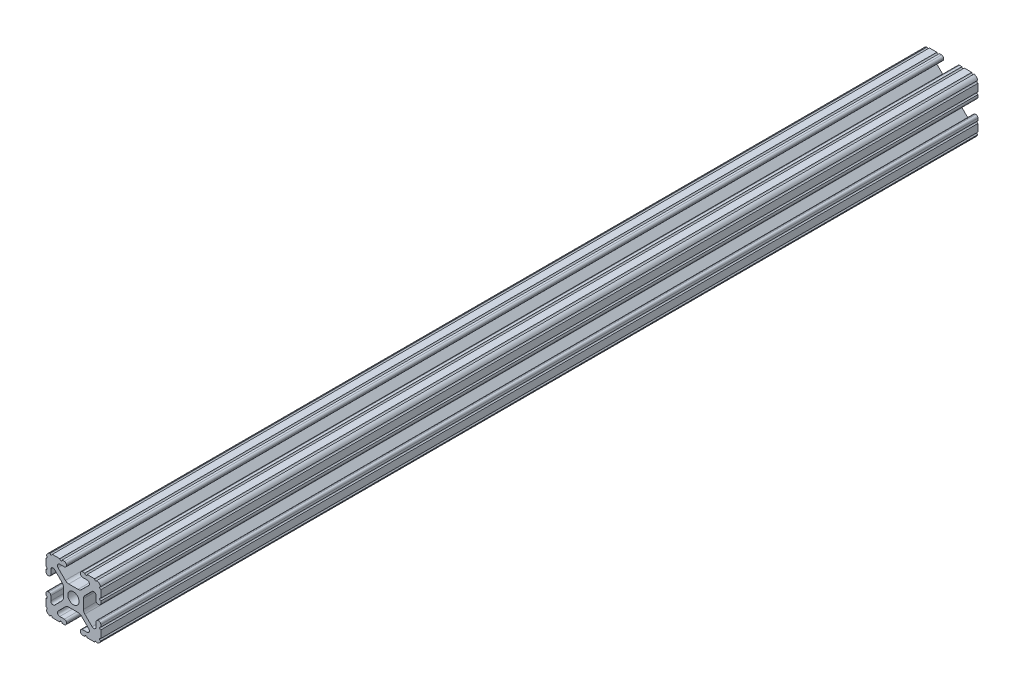
SolidWorks part; units mm, degrees
ref_plane "Front Plane" through (0, 0, 0) normal (0, 0, 1) x (1, 0, 0)
ref_plane "Top Plane" through (0, 0, 0) normal (0, 1, 0) x (1, 0, 0)
ref_plane "Right Plane" through (0, 0, 0) normal (1, 0, 0) x (0, 0, -1)
sketch "Sketch2" plane through (0, 0, 0) normal (0, 0, 1) x (1, 0, 0)
  line L0 (0, 12.7) -> (0, -12.7) construction
  line L1 (-12.7, 0) -> (12.7, 0) construction
  line L2 (3.2512, -12.7) -> (12.7, -12.7)
  line L3 (12.7, -12.7) -> (12.7, -3.2512)
  line L4 (3.2512, -12.7) -> (3.2512, -10.4902)
  line L5 (3.2512, -10.4902) -> (8.9276, -10.4902)
  line L6 (8.9276, -10.4902) -> (3.0856, -4.6482)
  line L7 (0, 0) -> (12.7, -12.7) construction
  line L8 (12.7, -3.2512) -> (10.4902, -3.2512)
  line L9 (10.4902, -3.2512) -> (10.4902, -8.9276)
  line L10 (10.4902, -8.9276) -> (4.6482, -3.0856)
  circle A0 centre (0, 0) radius 2.6035
  arc A1 (6.3485, -10.4902) -> (7.1039, -8.6665) centre (6.3485, -9.4219) ccw construction
  point P8 (0, -4.6482)
  dimension "Center Hole Diameter" = 5.207
  dimension "Rail Height" = 25.4
  dimension "Rail Width" = 25.4
  dimension "T-Slot Width" = 6.5024
  dimension "Slot Inner Width" = 14.8336
  dimension "Thickness" = 2.2098
  dimension "Slot Depth" = 5.842
  dimension "D1" = 2.2098
sketch "Sketch3" plane through (0, 0, 0) normal (1, 0, 0) x (0, 0, -1)
  line L0 (-203.2, -12.7) -> (203.2, -12.7) construction
  line L1 (-177.8, 0) -> (177.8, 0) construction
  dimension "Length" = 406.4
  dimension "D1" = 25.4
sketch "Sketch4" plane through (0, 0, 0) normal (0, 0, 1) x (1, 0, 0)
  line L0 (4.1904, -12.7) -> (10.1173, -12.7)
  line L1 (3.2512, -12.7) -> (12.7, -12.7) construction
  line L2 (3.2512, -12.7) -> (3.2512, -10.4902) construction
  line L3 (3.2512, -10.4902) -> (8.9276, -10.4902) construction
  line L4 (3.2512, -11.4294) -> (3.2512, -11.7608)
  line L5 (4.1904, -10.4902) -> (6.3485, -10.4902)
  line L6 (0, -4.6482) -> (2.164, -4.6482)
  line L7 (8.9276, -10.4902) -> (3.0856, -4.6482) construction
  line L8 (3.7373, -5.2999) -> (7.1039, -8.6665)
  line L9 (12.7, -12.7) -> (12.7, -3.2512) construction
  line L10 (10.4902, -8.9276) -> (4.6482, -3.0856) construction
  line L11 (10.4902, -3.2512) -> (10.4902, -8.9276) construction
  line L12 (10.4902, -6.3485) -> (10.4902, -4.1904)
  line L13 (12.7, -3.2512) -> (10.4902, -3.2512) construction
  line L14 (11.4294, -3.2512) -> (11.7608, -3.2512)
  line L15 (12.7, -4.1904) -> (12.7, -10.1173)
  line L16 (8.6665, -7.1039) -> (5.2999, -3.7373)
  line L17 (4.6482, 0) -> (4.6482, -2.164)
  line L18 (-12.7, 0) -> (12.7, 0) construction
  line L19 (0, -4.6482) -> (0, -2.6035)
  line L20 (0, 12.7) -> (0, -12.7) construction
  line L21 (4.6482, 0) -> (2.6035, 0)
  arc A0 (3.2512, -11.7608) -> (4.1904, -12.7) centre (4.1904, -11.7608) ccw
  arc A2 (3.2512, -11.4294) -> (4.1904, -10.4902) centre (4.1904, -11.4294) cw
  arc A3 (6.3485, -10.4902) -> (7.1039, -8.6665) centre (6.3485, -9.4219) ccw
  arc A4 (2.164, -4.6482) -> (3.7373, -5.2999) centre (2.164, -6.8732) cw
  arc A5 (10.1173, -12.7) -> (12.7, -10.1173) centre (10.1173, -10.1173) ccw
  arc A6 (8.6665, -7.1039) -> (10.4902, -6.3485) centre (9.4219, -6.3485) ccw
  arc A7 (10.4902, -4.1904) -> (11.4294, -3.2512) centre (11.4294, -4.1904) cw
  arc A8 (11.7608, -3.2512) -> (12.7, -4.1904) centre (11.7608, -4.1904) cw
  arc A9 (5.2999, -3.7373) -> (4.6482, -2.164) centre (6.8732, -2.164) cw
  circle A10 centre (0, 0) radius 2.6035 construction
  arc A11 (0, -2.6035) -> (2.6035, 0) centre (0, 0) ccw
  dimension "D1" = 2.5827
  dimension "D2" = 2.225
  dimension "D3" = 0.9392
extrude "Boss-Extrude1" add sketch "Sketch4" along normal mid plane 406.4
sketch "Sketch5" plane through (0, 0, 0) normal (0, 0, 1) x (1, 0, 0)
  line L0 (3.2512, -12.7) -> (12.7, -12.7) construction
  line L1 (4.1904, -10.4902) -> (6.3485, -10.4902) construction
  line L3 (0, 0) -> (12.7, -12.7) construction
  line L4 (6.3485, -10.4902) -> (6.3485, -12.7) construction
  line L5 (8.9276, -10.4902) -> (3.0856, -4.6482) construction
  circle A0 centre (10.3562, -12.7) radius 0.5524
  circle A1 centre (5.796, -12.7) radius 0.5524
  circle A2 centre (12.7, -10.3562) radius 0.5524
  circle A3 centre (12.7, -5.796) radius 0.5524
  point P10 (5.2694, -10.4902)
  point P12 (9.4219, -6.3485)
  dimension "D1" = 1.1049
extrude "Cut-Extrude1" cut sketch "Sketch5" against normal through all both and the other way through all
mirror "Mirror1" about plane through (0, 0, 0) normal (1, 0, 0) of bodies 137 134
mirror "Mirror2" about plane through (0, 0, 0) normal (0, 1, 0) of bodies 135
equation "\"D1@Boss-Extrude1\"=\"Length@Sketch3\""
equation "\"D1@Sketch2\"=\"Thickness@Sketch2\""
equation "\"D2@Sketch4\"=\"Slot Inner Width@Sketch2\"*0.15"
equation "\"D1@Sketch4\"=\"D3@Sketch4\"*2.75"
equation "\"D3@Sketch4\"=\"Thickness@Sketch2\"*0.425"
equation "\"D1@Sketch5\"=\"Thickness@Sketch2\"*0.5"
